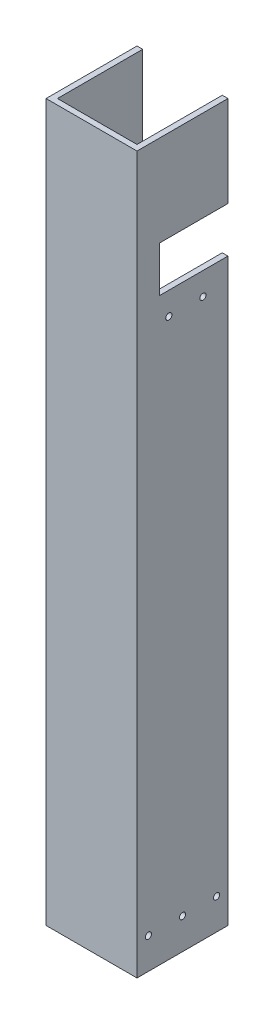
SolidWorks part; units mm, degrees
ref_plane "Front Plane" through (0, 0, 0) normal (0, 0, 1) x (1, 0, 0)
ref_plane "Top Plane" through (0, 0, 0) normal (0, 1, 0) x (1, 0, 0)
ref_plane "Right Plane" through (0, 0, 0) normal (1, 0, 0) x (0, 0, -1)
sketch "Sketch1" plane through (0, 0, 0) normal (0, 1, 0) x (1, 0, 0)
  line L0 (0, 0) -> (0, -50.8)
  line L1 (0, -50.8) -> (50.8, -50.8)
  line L2 (50.8, -50.8) -> (50.8, 0)
  line L3 (50.8, 0) -> (47.625, 0)
  line L4 (47.625, 0) -> (47.625, -47.625)
  line L5 (47.625, -47.625) -> (3.175, -47.625)
  line L6 (3.175, -47.625) -> (3.175, 0)
  line L7 (3.175, 0) -> (0, 0)
  dimension "D1" = 50.8
  dimension "D2" = 3.175
  dimension "D3" = 3.175
  dimension "D4" = 3.175
  dimension "D5" = 50.8
extrude "Boss-Extrude1" add sketch "Sketch1" along normal blind 400
sketch "Sketch2" plane through (0, 0, 0) normal (0, 0, -1) x (-1, 0, 0)
  line L0 (-50.8, 400) -> (-50.8, 0) construction
  line L1 (-47.625, 400) -> (-47.625, 0) construction
  line L2 (-50.8, 349.2) -> (-47.625, 349.2)
  line L3 (-50.8, 349.2) -> (-50.8, 323.8)
  line L4 (-50.8, 323.8) -> (-47.625, 323.8)
  line L5 (-47.625, 349.2) -> (-47.625, 323.8)
  line L6 (-50.8, 400) -> (-47.625, 400) construction
  dimension "D1" = 25.4
  dimension "D2" = 50.8
extrude "Cut-Extrude1" cut sketch "Sketch2" against normal blind 38.1
hole_wizard "Tap Drill for #8-32 Tap1" positions "Sketch4" profile "Sketch3" hole size "#8-32" standard "ANSI Inch" end condition through all
sketch "Sketch4" plane through (50.8, 0, 0) normal (1, 0, 0) x (0, 0, -1)
  point P0 (-44.45, 17.3)
  point P3 (-25.4, 17.3)
  point P6 (-6.35, 17.3)
sketch "Sketch3" plane through (50.8, 17.3, 44.45) normal (0, 1, 0) x (0, 0, -1)
  line L0 (0, 0) -> (0, 50.8)
  line L1 (0, 50.8) -> (1.7272, 50.8)
  line L2 (1.7272, 50.8) -> (1.7272, 0)
  line L5 (1.7272, 0) -> (0, 0)
  line L11 (0, -6.35) -> (0, 107.95) construction
  dimension "Thru Hole Dia." = 3.4544
  dimension "Thru Hole Depth" = 50.8
hole_wizard "Tap Drill for #8-32 Tap2" positions "Sketch6" profile "Sketch5" hole size "#8-32" standard "ANSI Inch"
sketch "Sketch6" plane through (50.8, 0, 0) normal (1, 0, 0) x (0, 0, -1)
  point P0 (-33.02, 311.1)
  point P3 (-13.97, 311.1)
sketch "Sketch5" plane through (50.8, 311.1, 33.02) normal (0, 1, 0) x (0, 0, -1)
  line L0 (0, 0) -> (0, 3.175)
  line L1 (0, 3.175) -> (1.7272, 3.175)
  line L2 (1.7272, 3.175) -> (1.7272, 0)
  line L5 (1.7272, 0) -> (0, 0)
  line L11 (0, -6.35) -> (0, 107.95) construction
  dimension "Thru Hole Dia." = 3.4544
  dimension "Thru Hole Depth" = 3.175
